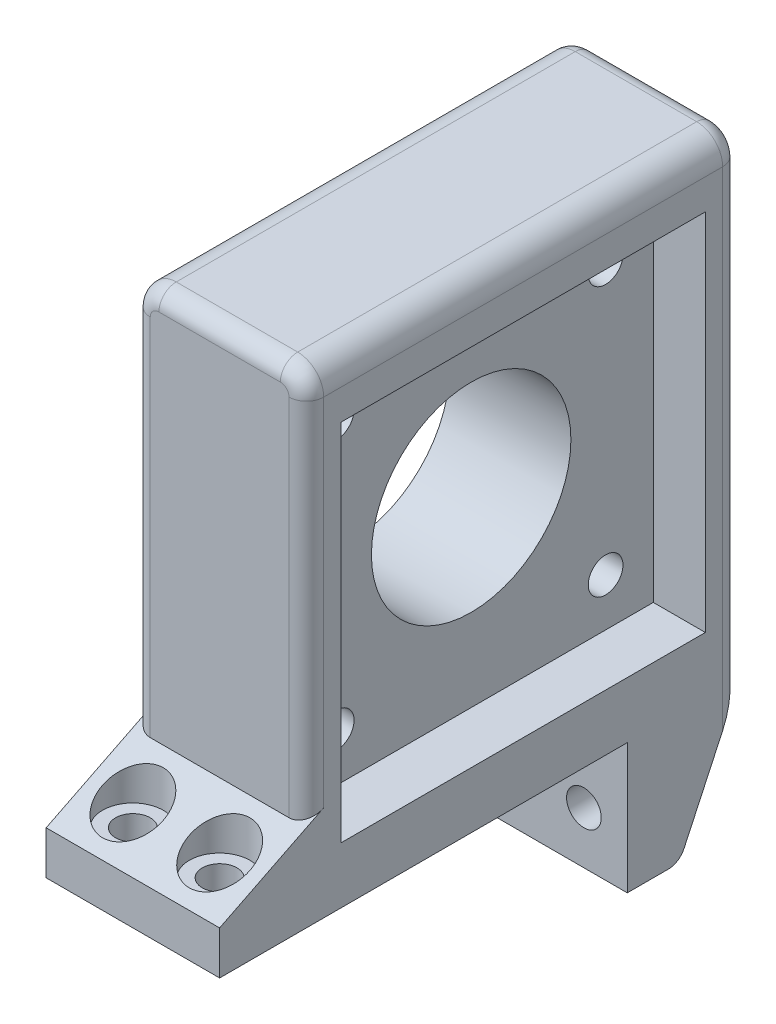
SolidWorks part; units mm, degrees
ref_plane "Front Plane" through (0, 0, 0) normal (0, 0, 1) x (1, 0, 0)
ref_plane "Top Plane" through (0, 0, 0) normal (0, 1, 0) x (1, 0, 0)
ref_plane "Right Plane" through (0, 0, 0) normal (1, 0, 0) x (0, 0, -1)
sketch "Sketch1" plane through (0, 0, 0) normal (0, 1, 0) x (1, 0, 0)
  line L1 (0, 0) -> (-20, 0)
  line L2 (0, 0) -> (0, -50)
  line L3 (0, -50) -> (-20, -50)
  line L4 (-20, 0) -> (-20, -50)
  dimension "D1" = 20
  dimension "D2" = 50
extrude "Boss-Extrude1" add sketch "Sketch1" along normal blind 70
sketch "Sketch2" plane through (0, 0, 0) normal (1, 0, 0) x (0, 0, -1)
  line L0 (-50, 70) -> (0, 70) construction
  line L1 (0, 70) -> (0, 0) construction
  line L2 (0, 42.5) -> (-50, 42.5) construction
  line L3 (-25, 70) -> (-25, 0) construction
  line L4 (-25, 70) -> (-25, 0) construction
  line L7 (-50, 70) -> (-50, 0) construction
  circle A0 centre (-9.5, 58) radius 2
  circle A4 centre (-25, 42.5) radius 11.5
  circle A5 centre (-9.5, 27) radius 2
  circle A8 centre (-40.5, 27) radius 2
  circle A9 centre (-40.5, 58) radius 2
  dimension "D1" = 4
  dimension "D2" = 12
  dimension "D3" = 15.5
  dimension "D6" = 23
  dimension "D7" = 0
  dimension "D8" = 0
  dimension "D4" = 15.5
  dimension "D5" = 0
extrude "Cut-Extrude2" cut sketch "Sketch2" against normal blind 60
sketch "Sketch4" plane through (0, 0, 0) normal (1, 0, 0) x (0, 0, -1)
  line L1 (-50, 0) -> (-13, 0)
  line L2 (-50, 0) -> (-50, 15)
  line L3 (-50, 15) -> (-13, 15)
  line L4 (-13, 0) -> (-13, 15)
  circle A0 centre (-25, 42.5) radius 11.5 construction
  dimension "D1" = 15
  dimension "D2" = 12
extrude "Cut-Extrude3" cut sketch "Sketch4" against normal blind 60
sketch "Sketch8" plane through (0, 0, 0) normal (0, 0, -1) x (-1, 0, 0)
  line L0 (0, 0) -> (20, 0) construction
  line L1 (20, 70) -> (20, 0) construction
  line L2 (0, 70) -> (0, 0) construction
  circle A0 centre (15, 6) radius 2
  circle A1 centre (5, 6) radius 2
  dimension "D1" = 4
  dimension "D2" = 6
  dimension "D3" = 5
  dimension "D4" = 4
  dimension "D5" = 0
  dimension "D6" = 5
extrude "Cut-Extrude5" cut sketch "Sketch8" against normal blind 15
sketch "Sketch9" plane through (0, 0, 0) normal (1, 0, 0) x (0, 0, -1)
  line L0 (0, 42.5) -> (-50, 42.5) construction
  line L1 (-4, 63.5) -> (-46, 63.5)
  line L2 (-4, 63.5) -> (-4, 21.5)
  line L3 (-4, 21.5) -> (-46, 21.5)
  line L4 (-46, 63.5) -> (-46, 21.5)
  line L5 (0, 70) -> (0, 0) construction
  line L6 (-50, 70) -> (-50, 15) construction
  line L7 (-25, 70) -> (-25, 15) construction
  line L8 (-50, 70) -> (0, 70) construction
  line L9 (-13, 15) -> (-50, 15) construction
  circle A0 centre (-25, 42.5) radius 11.5 construction
  dimension "D1" = 0
  dimension "D2" = 42
  dimension "D3" = 21
  dimension "D4" = 42
  dimension "D5" = 21
  dimension "D6" = 0
extrude "Cut-Extrude6" cut sketch "Sketch9" against normal blind 6
sketch "Sketch11" plane through (0, 0, 0) normal (1, 0, 0) x (0, 0, -1)
  line L7 (-7, 0) -> (0, 0)
  line L8 (-13, 0) -> (0, 0) construction
  line L9 (0, 0) -> (0, 15)
  line L10 (0, 70) -> (0, 0) construction
  line L11 (0, 15) -> (-7, 0)
  line L12 (-13, 15) -> (-50, 15) construction
  dimension "D1" = 0
  dimension "D2" = 6
extrude "Cut-Extrude8" cut sketch "Sketch11" against normal blind 30
sketch "Sketch12" plane through (0, 0, 50) normal (0, 0, 1) x (1, 0, 0)
  line L0 (-20, 70) -> (-20, 15) construction
  line L1 (0, 15) -> (-20, 15)
  line L2 (0, 15) -> (0, 20)
  line L3 (0, 20) -> (-20, 20)
  line L4 (-20, 15) -> (-20, 20)
  dimension "D1" = 5
extrude "Boss-Extrude2" add sketch "Sketch12" along normal blind 10
sketch "Sketch14" plane through (0, 0, 0) normal (1, 0, 0) x (0, 0, -1)
  line L0 (-50, 20) -> (-60, 20)
  line L1 (-60, 20) -> (-50, 20) construction
  line L2 (-60, 20) -> (-50, 25)
  line L3 (-50, 70) -> (-50, 20) construction
  line L4 (-50, 25) -> (-50, 20)
  dimension "D1" = 5
extrude "Boss-Extrude3" add sketch "Sketch14" against normal up to vertex (20 mm away)
sketch "Sketch15" plane through (0, 15, 0) normal (0, -1, 0) x (-1, 0, 0)
  line L0 (0, -13) -> (0, -60) construction
  line L1 (20, -13) -> (20, -60) construction
  line L2 (20, -60) -> (0, -60) construction
  circle A0 centre (5, -55) radius 2
  circle A1 centre (15, -55) radius 2
  dimension "D1" = 4
  dimension "D2" = 4
  dimension "D3" = 5
  dimension "D4" = 5
  dimension "D5" = 5
  dimension "D6" = 5
extrude "Cut-Extrude9" cut sketch "Sketch15" against normal blind 10
sketch "Sketch17" plane through (0, 0, 0) normal (0, 0, -1) x (-1, 0, 0)
  circle A0 centre (15, 6) radius 3.5
  circle A1 centre (5, 6) radius 3.5
  dimension "D1" = 7
  dimension "D2" = 7
extrude "Cut-Extrude11" cut sketch "Sketch17" against normal blind 8
sketch "Sketch18" plane through (0, 70, 0) normal (0, 1, 0) x (1, 0, 0)
  circle A0 centre (-15, -55) radius 3.5
  circle A1 centre (-5, -55) radius 3.5
  dimension "D1" = 7
  dimension "D2" = 7
extrude "Cut-Extrude12" cut sketch "Sketch18" against normal blind 50
fillet "Fillet2" radius 3 1 edges at (0, 70, 25)
fillet "Fillet3" radius 3 1 edges at (-20, 70, 25)
fillet "Fillet4" radius 2 5 edges at (-20, 46, 50) (-19.1213, 69.1213, 50) (0, 46, 50) (-0.8787, 69.1213, 50) (-10, 70, 50)
fillet "Fillet5" radius 2 5 edges at (0, 41, 0) (-0.8787, 69.1213, 0) (-20, 41, 0) (-19.1213, 69.1213, 0) (-10, 70, 0)
fillet "Fillet6" radius 2 1 edges at (-10, 0, 7)
